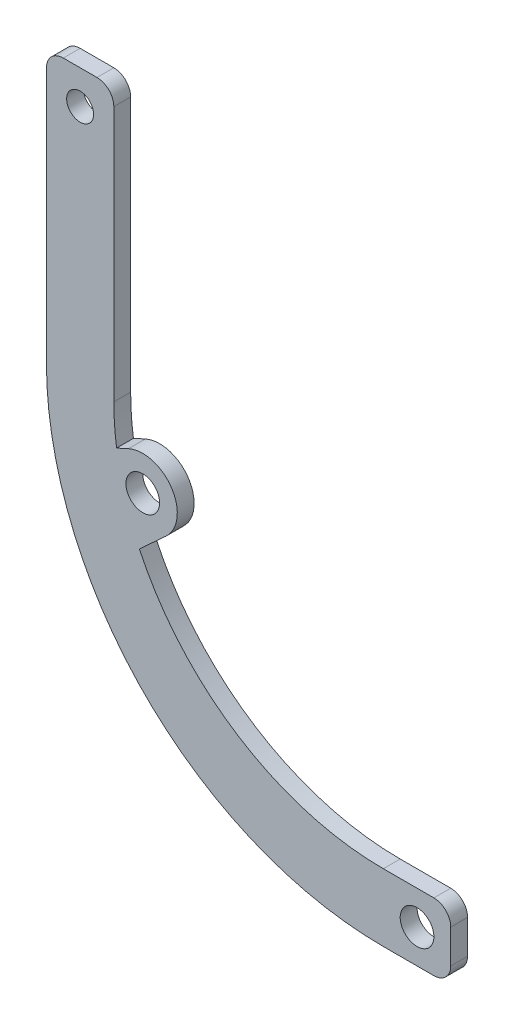
SolidWorks part; units mm, degrees
ref_plane "Front Plane" through (0, 0, 0) normal (0, 0, 1) x (1, 0, 0)
ref_plane "Top Plane" through (0, 0, 0) normal (0, 1, 0) x (1, 0, 0)
ref_plane "Right Plane" through (0, 0, 0) normal (1, 0, 0) x (0, 0, -1)
sketch "Sketch1" plane through (0, 0, 0) normal (0, 0, 1) x (1, 0, 0)
  line L0 (-10, 10) -> (10, 10)
  line L1 (10, 10) -> (10, -10)
  line L2 (10, -10) -> (-10, -10)
  line L4 (-110, 90) -> (-110, 170.8903)
  line L5 (-110, 170.8903) -> (-90, 170.8903)
  line L12 (0, 0) -> (67.8578, 0) construction
  line L13 (-85.9774, 80) -> (-110, 80) construction
  line L14 (-100, 170.8903) -> (-100, 80) construction
  line L15 (-90, 170.8903) -> (-90, 90)
  line L17 (0, 0) -> (0, 249.807) construction
  line L18 (-89.1752, 78.5417) -> (-85.6507, 80.145)
  line L19 (-82.4128, 55.9943) -> (-74.4833, 63.2607)
  line L20 (0, 0) -> (-39.6944, 40.4963) construction
  line L24 (-45.864, 83.5583) -> (-66.656, 76.1045) construction
  line L33 (-81.4071, 70.8164) -> (-101.5271, 63.6036) construction
  line L45 (-84.3477, 69.7623) -> (-45.864, 83.5583) construction
  line L51 (-70.2821, 96.0509) -> (-56.7837, 58.3973) construction
  line L52 (-96.6397, 86.602) -> (-80.6369, 92.3389) construction
  line L53 (-96.6397, 86.602) -> (-87.5222, 61.1689) construction
  line L54 (-83.1413, 48.9484) -> (-67.1385, 54.6853) construction
  line L55 (-80.6369, 92.3389) -> (-67.1385, 54.6853) construction
  line L56 (-63.5329, 77.2241) -> (-146.0728, 47.6345) construction
  line L58 (-30, 20) -> (30, 20) construction
  line L59 (-30, 20) -> (-30, 180) construction
  line L60 (-30, 180) -> (30, 180) construction
  line L61 (30, 20) -> (30, 180) construction
  line L62 (-30, 20) -> (30, 180) construction
  line L63 (-30, 180) -> (30, 20) construction
  line L64 (-8.2959, 12.0407) -> (-64.7763, -8.2069) construction
  line L65 (-8.2959, 12.0407) -> (-62.2896, 162.6551) construction
  line L66 (-62.2896, 162.6551) -> (-118.77, 142.4075) construction
  line L67 (-64.7763, -8.2069) -> (-118.77, 142.4075) construction
  line L68 (-8.2959, 12.0407) -> (-118.77, 142.4075) construction
  line L69 (-62.2896, 162.6551) -> (-64.7763, -8.2069) construction
  circle A0 centre (0, 0) radius 5
  circle A1 centre (-100, 160.8903) radius 4
  arc A3 (-93.1578, 80) -> (41.9046, 115.4226) centre (0, 0) cw construction
  arc A9 (-110, 90) -> (-10, -10) centre (-10, 90) ccw
  arc A10 (-89.3692, 100.0265) -> (-89.1752, 78.5417) centre (-10, 90) ccw construction
  arc A12 (-90, 90) -> (-89.1752, 78.5417) centre (-10, 90) ccw
  circle A13 centre (-80.6369, 92.3389) radius 11 construction
  circle A14 centre (-67.1385, 54.6853) radius 11 construction
  arc A15 (-63.5329, 77.2241) -> (0, 100) centre (0, 0) cw construction
  circle A16 centre (0, 100) radius 70 construction
  circle A17 centre (-81.4071, 70.8164) radius 5
  arc A18 (-85.6507, 80.145) -> (-74.4833, 63.2607) centre (-81.4071, 70.8164) cw
  arc A19 (-82.4128, 55.9943) -> (-10, 10) centre (-10, 90) ccw
  arc A20 (-82.4128, 55.9943) -> (-10, 10) centre (-10, 90) ccw construction
  circle A21 centre (40, 210) radius 7 construction
  arc A22 (-150.569, 108.2366) -> (0, 185.4352) centre (0, 0) cw construction
  point P32 (-73.8877, 73.5121)
  point P52 (0, 0)
  point P53 (-63.5329, 77.2241)
  point P58 (-220.9502, 90)
  point P59 (-63.5329, 77.2241)
  point P63 (-63.5329, 77.2241)
  point P67 (-100, 162.6551)
  point P68 (0, 0)
  point P69 (-154.7149, 111.2169)
  point P70 (0, 0)
  dimension "D1" = 10
  dimension "D13" = 8
  dimension "D7" = 60
  dimension "D27" = 22
  dimension "D22" = 100
  dimension "D23" = 140
  dimension "D16" = 14
  dimension "D2" = 10
  dimension "D3" = 10
  dimension "D4" = 20
  dimension "D5" = 93.1578
  dimension "D6" = 100
  dimension "D8" = 20
  dimension "D9" = 80
  dimension "D10" = 40
  dimension "D11" = 80
  dimension "D14" = 10
  dimension "D15" = 210
  dimension "D17" = 160
  dimension "D18" = 60
  dimension "D24" = 17
  dimension "D25" = 40
  dimension "D26" = 20
extrude "Boss-Extrude1" add sketch "Sketch1" along normal blind 5
fillet "Fillet3" radius 5 4 edges at (10, -10, 2.5) (10, 10, 2.5) (-90, 170.8903, 2.5) (-110, 170.8903, 2.5)
